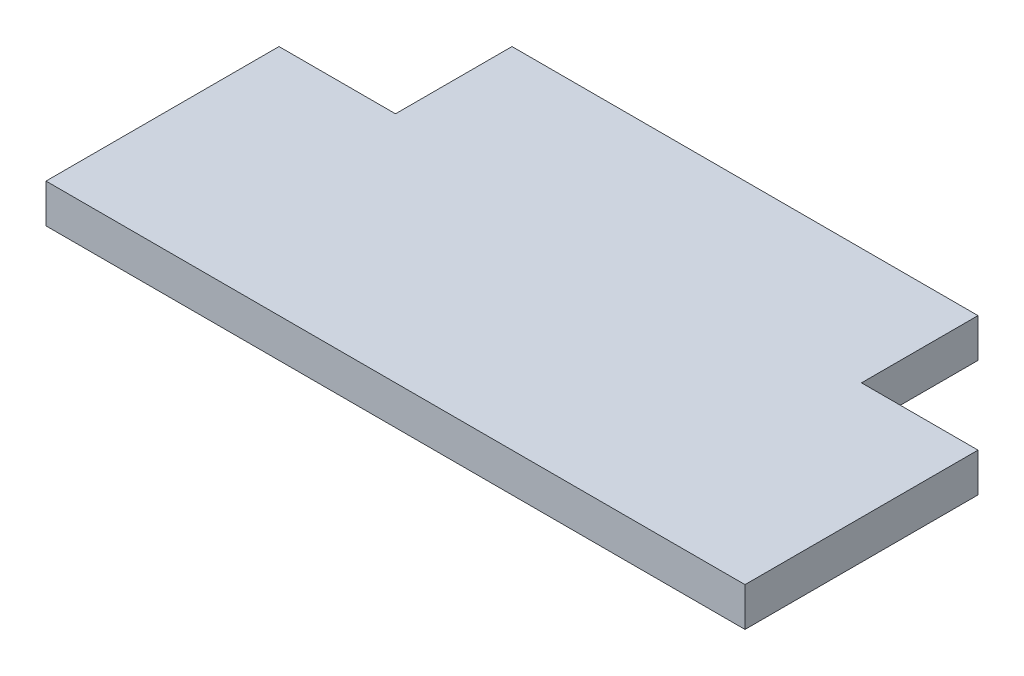
SolidWorks part; units mm, degrees
ref_plane "Front Plane" through (0, 0, 0) normal (0, 0, 1) x (1, 0, 0)
ref_plane "Top Plane" through (0, 0, 0) normal (0, 1, 0) x (1, 0, 0)
ref_plane "Right Plane" through (0, 0, 0) normal (1, 0, 0) x (0, 0, -1)
sketch "Sketch1" plane through (0, 0, 0) normal (0, 1, 0) x (1, 0, 0)
  line L0 (0, -1006.6389) -> (0, 1032.8882) construction
  line L1 (914.4, -304.8) -> (-914.4, -304.8)
  line L2 (914.4, -304.8) -> (914.4, 304.8)
  line L3 (914.4, 304.8) -> (-914.4, 304.8)
  line L4 (-914.4, -304.8) -> (-914.4, 304.8)
  line L5 (914.4, -304.8) -> (-914.4, 304.8) construction
  line L6 (914.4, 304.8) -> (-914.4, -304.8) construction
  line L12 (-609.6, 304.8) -> (609.6, 304.8)
  line L13 (-609.6, 304.8) -> (-609.6, 609.6)
  line L14 (-609.6, 609.6) -> (609.6, 609.6)
  line L15 (609.6, 304.8) -> (609.6, 609.6)
  point P0 (0, 0)
  point P12 (0, 1032.8882)
  point P13 (0, 609.6)
  dimension "D1" = 609.6
  dimension "D2" = 1828.8
  dimension "D3" = 1219.2
  dimension "D4" = 304.8
extrude "Boss-Extrude1" add sketch "Sketch1" along normal blind 101.6 contours L4 L1 L2 L3 | L15 L1 L13 L14
curve "Curve1"
  spline degree 3 poles (0, 25.4, 0.0064) (0, 25.2657, 0.0346) (0, 24.9974, 0.0911) (0, 24.5944, 0.1721) (0, 24.1917, 0.2509) (0, 23.7893, 0.3278) (0, 23.3874, 0.4029) (0, 22.9859, 0.4765) (0, 22.5851, 0.5485) (0, 22.1849, 0.619) (0, 21.7856, 0.688) (0, 21.3872, 0.7554) (0, 20.9898, 0.8212) (0, 20.5935, 0.8853) (0, 20.1985, 0.9476) (0, 19.8047, 1.0082) (0, 19.4123, 1.067) (0, 19.0215, 1.124) (0, 18.6322, 1.1792) (0, 18.2447, 1.2326) (0, 17.859, 1.2841) (0, 17.4751, 1.3339) (0, 17.0933, 1.382) (0, 16.7135, 1.4283) (0, 16.3359, 1.4729) (0, 15.9606, 1.5158) (0, 15.5877, 1.5571) (0, 15.2173, 1.5967) (0, 14.8494, 1.6346) (0, 14.4842, 1.6709) (0, 14.1217, 1.7054) (0, 13.7621, 1.7383) (0, 13.4054, 1.7695) (0, 13.0517, 1.7989) (0, 12.7011, 1.8265) (0, 12.3537, 1.8522) (0, 12.0097, 1.8761) (0, 11.6689, 1.8981) (0, 11.3317, 1.918) (0, 10.9979, 1.936) (0, 10.6678, 1.9519) (0, 10.3414, 1.9657) (0, 10.0188, 1.9774) (0, 9.7001, 1.9869) (0, 9.3853, 1.9942) (0, 9.0746, 1.9993) (0, 8.7679, 2.0022) (0, 8.4655, 2.0029) (0, 8.1673, 2.0014) (0, 7.8734, 1.9977) (0, 7.584, 1.9918) (0, 7.2991, 1.9837) (0, 7.0187, 1.9735) (0, 6.7429, 1.9612) (0, 6.4718, 1.9468) (0, 6.2055, 1.9304) (0, 5.944, 1.912) (0, 5.6874, 1.8917) (0, 5.4358, 1.8694) (0, 5.1892, 1.8454) (0, 4.9477, 1.8195) (0, 4.7114, 1.792) (0, 4.4802, 1.7628) (0, 4.2543, 1.7319) (0, 4.0338, 1.6995) (0, 3.8186, 1.6656) (0, 3.6089, 1.6303) (0, 3.4046, 1.5936) (0, 3.2059, 1.5556) (0, 3.0127, 1.5163) (0, 2.8252, 1.4759) (0, 2.6434, 1.4343) (0, 2.4673, 1.3917) (0, 2.297, 1.3481) (0, 2.1325, 1.3035) (0, 1.9738, 1.2581) (0, 1.8211, 1.2119) (0, 1.6742, 1.1649) (0, 1.5334, 1.1173) (0, 1.3985, 1.0691) (0, 1.2697, 1.0204) (0, 1.147, 0.9712) (0, 1.0304, 0.9215) (0, 0.9199, 0.8715) (0, 0.8155, 0.8212) (0, 0.7173, 0.7706) (0, 0.6254, 0.7198) (0, 0.5396, 0.6689) (0, 0.4601, 0.6178) (0, 0.3869, 0.5666) (0, 0.3199, 0.5153) (0, 0.2592, 0.4639) (0, 0.2049, 0.4126) (0, 0.1568, 0.3611) (0, 0.1151, 0.3097) (0, 0.0797, 0.2582) (0, 0.0507, 0.2067) (0, 0.0281, 0.1551) (0, 0.0119, 0.1034) (0, 0.0022, 0.0517) (0, -0.0011, 0.0014) (0, 0.0021, -0.0476) (0, 0.0119, -0.095) (0, 0.0281, -0.1421) (0, 0.0507, -0.1886) (0, 0.0797, -0.2345) (0, 0.1151, -0.2796) (0, 0.1568, -0.3238) (0, 0.2049, -0.3671) (0, 0.2593, -0.4092) (0, 0.32, -0.4502) (0, 0.387, -0.49) (0, 0.4602, -0.5285) (0, 0.5397, -0.5656) (0, 0.6255, -0.6013) (0, 0.7175, -0.6357) (0, 0.8157, -0.6686) (0, 0.92, -0.7001) (0, 1.0306, -0.7301) (0, 1.1472, -0.7588) (0, 1.2699, -0.786) (0, 1.3988, -0.8119) (0, 1.5336, -0.8364) (0, 1.6745, -0.8596) (0, 1.8213, -0.8815) (0, 1.974, -0.9021) (0, 2.1327, -0.9215) (0, 2.2972, -0.9397) (0, 2.4675, -0.9567) (0, 2.6436, -0.9725) (0, 2.8254, -0.9871) (0, 3.0129, -1.0006) (0, 3.206, -1.0129) (0, 3.4048, -1.0241) (0, 3.609, -1.0341) (0, 3.8188, -1.043) (0, 4.0339, -1.0507) (0, 4.2545, -1.0573) (0, 4.4804, -1.0628) (0, 4.7115, -1.0671) (0, 4.9478, -1.0703) (0, 5.1893, -1.0723) (0, 5.4359, -1.0732) (0, 5.6875, -1.073) (0, 5.9441, -1.0718) (0, 6.2056, -1.0694) (0, 6.4719, -1.0661) (0, 6.7429, -1.0617) (0, 7.0187, -1.0564) (0, 7.2991, -1.0502) (0, 7.584, -1.0431) (0, 7.8735, -1.0352) (0, 8.1673, -1.0265) (0, 8.4655, -1.017) (0, 8.7679, -1.0069) (0, 9.0746, -0.996) (0, 9.3853, -0.9846) (0, 9.7001, -0.9725) (0, 10.0188, -0.9599) (0, 10.3414, -0.9466) (0, 10.6678, -0.9328) (0, 10.9979, -0.9185) (0, 11.3316, -0.9035) (0, 11.6689, -0.888) (0, 12.0096, -0.8718) (0, 12.3537, -0.855) (0, 12.7011, -0.8375) (0, 13.0517, -0.8194) (0, 13.4053, -0.8005) (0, 13.762, -0.781) (0, 14.1217, -0.7608) (0, 14.4841, -0.7398) (0, 14.8494, -0.7181) (0, 15.2172, -0.6958) (0, 15.5877, -0.6729) (0, 15.9606, -0.6493) (0, 16.3359, -0.6253) (0, 16.7134, -0.6007) (0, 17.0932, -0.5758) (0, 17.475, -0.5506) (0, 17.8589, -0.5252) (0, 18.2446, -0.4996) (0, 18.6321, -0.4739) (0, 19.0214, -0.4481) (0, 19.4122, -0.4224) (0, 19.8046, -0.3966) (0, 20.1983, -0.3708) (0, 20.5934, -0.3449) (0, 20.9897, -0.3189) (0, 21.3871, -0.2926) (0, 21.7855, -0.2659) (0, 22.1848, -0.2386) (0, 22.585, -0.2108) (0, 22.9858, -0.1822) (0, 23.3872, -0.153) (0, 23.7892, -0.1231) (0, 24.1915, -0.0928) (0, 24.5941, -0.0626) (0, 24.997, -0.0331) (0, 25.2657, -0.0153) (0, 25.4, -0.0064) knots 0 0 0 0 0.007941 0.015868 0.023782 0.031684 0.039571 0.047444 0.055299 0.063136 0.070953 0.078747 0.086517 0.09426 0.101975 0.10966 0.117312 0.124931 0.132515 0.14006 0.147567 0.155033 0.162457 0.169836 0.17717 0.184456 0.191693 0.198879 0.206013 0.213092 0.220115 0.227081 0.233988 0.240834 0.247617 0.254336 0.260989 0.267575 0.274092 0.280538 0.286913 0.293214 0.299441 0.305592 0.311665 0.31766 0.323575 0.329409 0.33516 0.340829 0.346413 0.351912 0.357324 0.362648 0.367884 0.373031 0.378086 0.383051 0.387923 0.392702 0.397387 0.401977 0.406471 0.410868 0.415168 0.41937 0.423472 0.427475 0.431378 0.435179 0.438879 0.442477 0.445971 0.449362 0.45265 0.455833 0.458911 0.461884 0.464751 0.467513 0.470169 0.47272 0.475165 0.477504 0.479738 0.481867 0.483893 0.485816 0.487638 0.48936 0.490986 0.492517 0.493957 0.495311 0.496586 0.497786 0.498922 0.500002 0.50104 0.502047 0.503039 0.503952 0.504878 0.505831 0.506824 0.507866 0.508967 0.510136 0.51138 0.512704 0.514115 0.515615 0.517209 0.518901 0.520691 0.522584 0.524581 0.526682 0.528891 0.531207 0.533632 0.536166 0.538809 0.541562 0.544425 0.547398 0.550481 0.553673 0.556974 0.560384 0.563903 0.567529 0.571261 0.5751 0.579045 0.583094 0.587247 0.591503 0.595862 0.600321 0.60488 0.609539 0.614295 0.619148 0.624097 0.629141 0.634278 0.639507 0.644828 0.650237 0.655735 0.66132 0.666991 0.672745 0.678583 0.684501 0.690499 0.696575 0.702728 0.708956 0.715257 0.72163 0.728074 0.734587 0.741166 0.747811 0.75452 0.761292 0.768124 0.775014 0.781962 0.788966 0.796023 0.803132 0.810291 0.817498 0.824752 0.832051 0.839391 0.846773 0.854193 0.86165 0.869142 0.876666 0.884222 0.891806 0.899418 0.907055 0.914715 0.922398 0.9301 0.93782 0.945557 0.953308 0.961072 0.968847 0.97663 0.984418 0.99221 1 1 1 1
sketch "Sketch4" plane through (0, 0, 0) normal (1, 0, 0) x (0, 0, -1)
  line L0 (234.95, 48.4655) -> (234.95, 48.221)
  line L1 (234.95, 48.3433) -> (-254, 48.3661) construction
  line L2 (-254, 127.5432) -> (-254, -30.8109) construction
  line L3 (-304.8, 101.6) -> (-304.8, 0) construction
  spline S1 degree 3 poles (234.95, 48.4655) (232.3649, 49.0096) (227.1991, 50.0968) (219.442, 51.6554) (211.6903, 53.1737) (203.9444, 54.6529) (196.2066, 56.0993) (188.4786, 57.5152) (178.2031, 59.3616) (162.8599, 62.0395) (145.0179, 64.9952) (127.2744, 67.7617) (112.201, 69.9904) (92.3737, 72.761) (72.7299, 75.271) (53.2927, 77.531) (38.9864, 79.0872) (24.8776, 80.5156) (10.9804, 81.8148) (-2.6913, 82.9814) (-16.1237, 84.0098) (-31.4194, 85.0354) (-48.4471, 85.9576) (-67.0658, 86.6382) (-85.0012, 86.9408) (-102.2125, 86.8602) (-116.9489, 86.4488) (-129.3298, 85.8462) (-139.4883, 85.1779) (-149.2698, 84.3605) (-158.6645, 83.402) (-167.6629, 82.3107) (-176.2561, 81.0954) (-184.4353, 79.7653) (-192.1924, 78.3296) (-199.5196, 76.7979) (-205.3449, 75.4301) (-210.8089, 74.0307) (-214.957, 72.8783) (-218.9444, 71.6721) (-221.7707, 70.7685) (-224.4822, 69.8521) (-227.078, 68.9241) (-229.5575, 67.9857) (-231.9202, 67.0381) (-234.1655, 66.0824) (-236.2928, 65.1198) (-238.3016, 64.1511) (-240.1915, 63.1775) (-241.9619, 62.1998) (-243.6125, 61.2187) (-245.1429, 60.235) (-246.5528, 59.2494) (-247.8418, 58.2622) (-249.0097, 57.274) (-250.0563, 56.2849) (-250.9813, 55.2952) (-251.7844, 54.3048) (-252.4654, 53.3137) (-253.0238, 52.3216) (-253.4591, 51.3285) (-253.771, 50.3343) (-253.9577, 49.3391) (-254.0208, 48.3697) (-253.9587, 47.4271) (-253.7708, 46.5144) (-253.4593, 45.6086) (-253.0239, 44.7126) (-252.4655, 43.8292) (-251.7843, 42.9608) (-250.981, 42.1093) (-250.0557, 41.277) (-249.0087, 40.4654) (-247.8404, 39.6762) (-246.551, 38.9108) (-245.1408, 38.1703) (-243.61, 37.4556) (-241.9591, 36.7676) (-240.1883, 36.1066) (-238.2982, 35.473) (-236.2892, 34.8669) (-234.1617, 34.2882) (-231.9163, 33.7368) (-229.5534, 33.2123) (-227.0738, 32.7143) (-224.478, 32.2423) (-221.7665, 31.7958) (-218.9402, 31.3742) (-215.9997, 30.9771) (-212.9457, 30.6038) (-209.779, 30.2541) (-205.3357, 29.8113) (-199.5048, 29.3186) (-192.1786, 28.8249) (-184.4226, 28.4189) (-176.2445, 28.1007) (-167.6525, 27.8705) (-158.6552, 27.7281) (-149.2617, 27.6729) (-139.4814, 27.7026) (-129.3242, 27.8138) (-118.8003, 28.0014) (-107.9203, 28.2593) (-96.6951, 28.5808) (-85.136, 28.9592) (-73.2546, 29.3886) (-61.0628, 29.8646) (-48.5729, 30.385) (-31.3591, 31.1457) (-13.7915, 31.991) (4.1117, 32.9307) (17.8977, 33.6966) (31.9022, 34.5172) (48.5345, 35.5382) (65.3834, 36.6218) (82.4327, 37.7455) (97.2431, 38.729) (109.6745, 39.5526) (122.2121, 40.3788) (134.8434, 41.2068) (150.0737, 42.2045) (162.8214, 43.0517) (173.0582, 43.7494) (180.7607, 44.2854) (188.4767, 44.835) (196.2044, 45.3984) (203.9417, 45.9739) (211.6867, 46.557) (219.4374, 47.1373) (227.1914, 47.7067) (232.3639, 48.0496) (234.95, 48.221) knots 0 0 0 0 0.007941 0.015868 0.023782 0.031684 0.039571 0.047444 0.055299 0.070953 0.09426 0.10966 0.124931 0.14006 0.169836 0.184456 0.198879 0.213092 0.227081 0.240834 0.254336 0.267575 0.286913 0.305592 0.323575 0.340829 0.357324 0.367884 0.378086 0.387923 0.397387 0.406471 0.415168 0.423472 0.431378 0.438879 0.445971 0.449362 0.455833 0.458911 0.461884 0.464751 0.467513 0.470169 0.47272 0.475165 0.477504 0.479738 0.481867 0.483893 0.485816 0.487638 0.48936 0.490986 0.492517 0.493957 0.495311 0.496586 0.497786 0.498922 0.500002 0.50104 0.502047 0.503039 0.503952 0.504878 0.505831 0.506824 0.507866 0.508967 0.510136 0.51138 0.512704 0.514115 0.515615 0.517209 0.518901 0.520691 0.522584 0.524581 0.526682 0.528891 0.531207 0.533632 0.536166 0.538809 0.541562 0.544425 0.547398 0.550481 0.553673 0.556974 0.563903 0.571261 0.579045 0.587247 0.595862 0.60488 0.614295 0.624097 0.634278 0.644828 0.655735 0.666991 0.678583 0.690499 0.702728 0.715257 0.728074 0.75452 0.768124 0.781962 0.796023 0.810291 0.832051 0.846773 0.86165 0.876666 0.884222 0.899418 0.914715 0.9301 0.93782 0.945557 0.953308 0.961072 0.968847 0.97663 0.984418 0.99221 1 1 1 1
  point P6 (23.9535, 28.2996)
  point P7 (-254, 48.3661)
  dimension "D1" = 488.95
  dimension "D2" = 50.8
